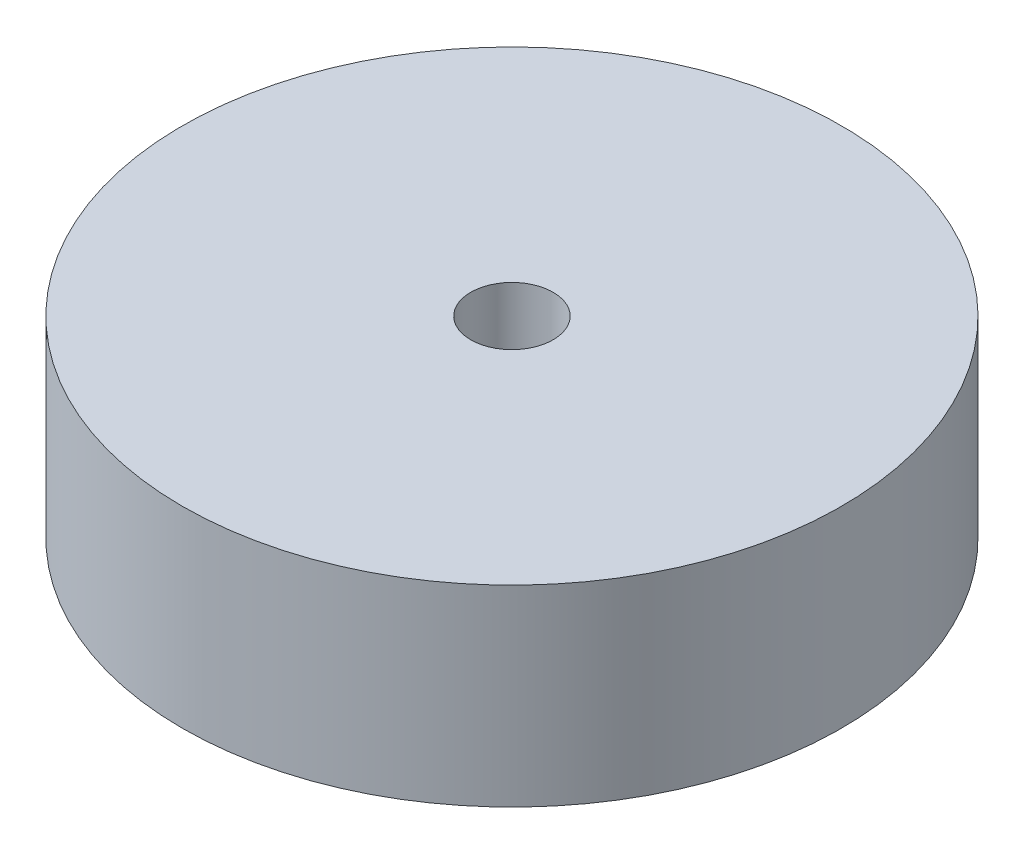
SolidWorks part; units mm, degrees
material "AISI 304"
ref_plane "Front Plane" through (0, 0, 0) normal (0, 0, 1) x (1, 0, 0)
ref_plane "Top Plane" through (0, 0, 0) normal (0, 1, 0) x (1, 0, 0)
ref_plane "Right Plane" through (0, 0, 0) normal (1, 0, 0) x (0, 0, -1)
sketch "Main Shape Profile" plane through (0, 0, 0) normal (0, 0, 1) x (1, 0, 0)
  line L0 (0, 0) -> (0, -35002.3512) construction
  line L1 (9.525, 44.45) -> (9.525, 25.4)
  line L2 (9.525, 25.4) -> (31.75, 25.4)
  line L3 (31.75, 25.4) -> (31.75, 15.24)
  line L4 (31.75, 15.24) -> (38.1, 15.24)
  line L5 (38.1, 15.24) -> (38.1, 8.89)
  line L6 (38.1, 8.89) -> (57.15, 8.89)
  line L7 (57.15, 8.89) -> (57.15, 0)
  line L8 (57.15, 0) -> (76.2, 0)
  line L9 (76.2, 0) -> (76.2, 44.45)
  line L10 (76.2, 44.45) -> (9.525, 44.45)
  dimension "Outer Flange Diameter" = 152.4
  dimension "Kerosene Plate Thickness" = 8.89
  dimension "LOX Plate Thickness" = 6.35
  dimension "LOX Manifold Thickness" = 10.16
  dimension "Total Shell Thickess" = 44.45
  dimension "Kerosene Plate Outer Diameter" = 114.3
  dimension "LOX Plate Diameter" = 76.2
  dimension "LOX Plate Inner Flange" = 6.35
  dimension "Hose Diameter" = 19.05
revolve "Main Shape" add sketch "Main Shape Profile" angle 360 about L0
